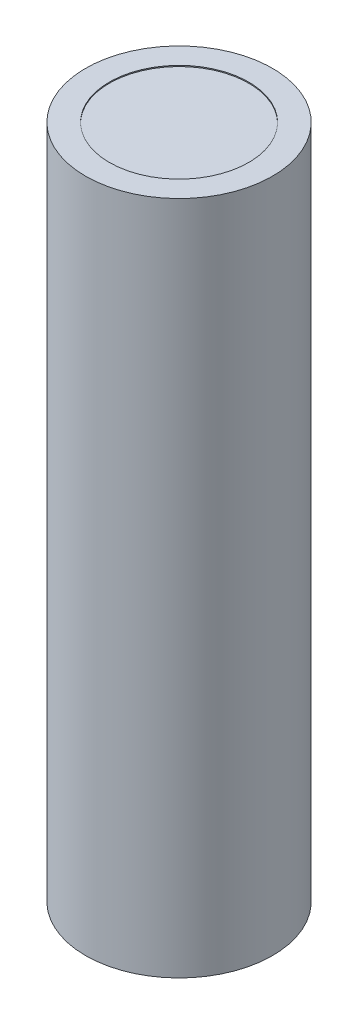
SolidWorks part; units mm, degrees
ref_plane "Front Plane" through (0, 0, 0) normal (0, 0, 1) x (1, 0, 0)
ref_plane "Top Plane" through (0, 0, 0) normal (0, 1, 0) x (1, 0, 0)
ref_plane "Right Plane" through (0, 0, 0) normal (1, 0, 0) x (0, 0, -1)
sketch "Sketch1" plane through (0, 0, 0) normal (0, 1, 0) x (1, 0, 0)
  circle A0 centre (0, 0) radius 9
  dimension "D1" = 18
extrude "Boss-Extrude1" add sketch "Sketch1" along normal blind 65
sketch "Sketch2" plane through (0, 65, 0) normal (0, 1, 0) x (1, 0, 0)
  circle A0 centre (0, 0) radius 6.7114
extrude "Cut-Extrude1" cut sketch "Sketch2" against normal blind 0.1
sketch "Sketch3" plane through (0, 0, 0) normal (0, -1, 0) x (1, 0, 0)
  circle A0 centre (0, 0) radius 7.3184
extrude "Cut-Extrude2" cut sketch "Sketch3" against normal blind 0.1
